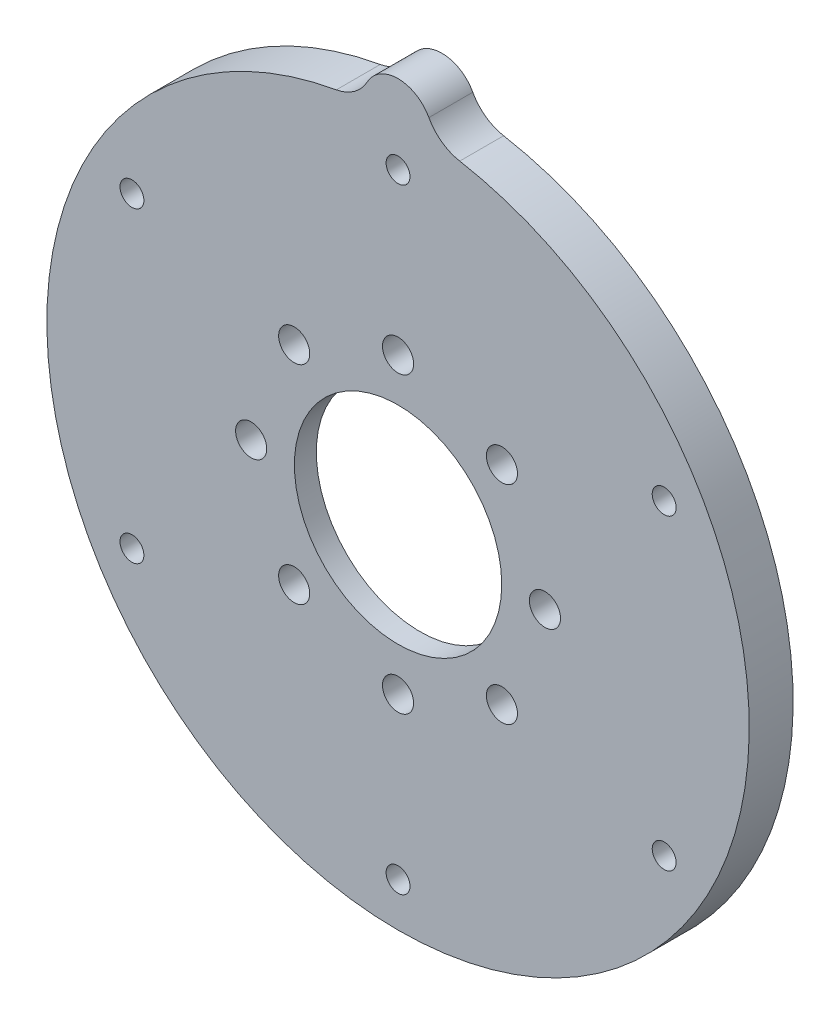
SolidWorks part; units mm, degrees
material "6061 Alloy"
ref_plane "Front Plane" through (0, 0, 0) normal (0, 0, 1) x (1, 0, 0)
ref_plane "Top Plane" through (0, 0, 0) normal (0, 1, 0) x (1, 0, 0)
ref_plane "Right Plane" through (0, 0, 0) normal (1, 0, 0) x (0, 0, -1)
sketch "Sketch1" plane through (0, 0, 0) normal (0, 0, 1) x (1, 0, 0)
  circle A0 centre (0, 0) radius 50.8
  circle A1 centre (0, 0) radius 15
  dimension "D1" = 101.6
  dimension "D2" = 30
extrude "Boss-Extrude1" add sketch "Sketch1" along normal blind 6.35
hole_wizard "M4 Clearance Hole1" positions "Sketch3" profile "Sketch4" hole size "M4" standard "Ansi Metric"
sketch "Sketch3" plane through (0, 0, 6.35) normal (0, 0, 1) x (1, 0, 0)
  point P0 (0, 21.25)
  dimension "D1" = 21.25
sketch "Sketch4" plane through (0, 21.25, 6.35) normal (1, 0, 0) x (0, -1, 0)
  line L0 (0, 0) -> (0, 26.7519)
  line L1 (0, 26.7519) -> (2.25, 25.4)
  line L2 (2.25, 25.4) -> (2.25, 0)
  line L5 (2.25, 0) -> (0, 0)
  line L10 (0, 26.7519) -> (-2.25, 25.4) construction
  line L11 (0, -6.35) -> (0, 107.95) construction
  dimension "Hole Dia." = 4.5
  dimension "Hole Depth" = 25.4
  dimension "Drill Angle" = 118
pattern_circular "CirPattern1" count 8 over 360 about axis through (0, 0, 0) along (0, 0, 1) of "M4 Clearance Hole1"
sketch "Sketch5" plane through (0, 0, 0) normal (0, 0, -1) x (-1, 0, 0)
  circle A0 centre (0, 0) radius 41.25
  dimension "D1" = 82.5
extrude "Cut-Extrude1" cut sketch "Sketch5" against normal offset from surface (3.175 mm away) 3.175 up to face at (-12.776, 15.026, 6.35)
chamfer "Chamfer1" distance 0.7874 angle 45 1 edges at (-41.25, 0, 0)
hole_wizard "#8-32 Tapped Hole1" positions "Sketch7" profile "Sketch8" tap size "#8-32" standard "Ansi Inch" end condition through all
sketch "Sketch7" plane through (0, 0, 6.35) normal (0, 0, 1) x (1, 0, 0)
  line L2 (0, 0) -> (0, 44.45) construction
  point P0 (0, 44.45)
  dimension "D1" = 44.45
sketch "Sketch8" plane through (0, 44.45, 6.35) normal (1, 0, 0) x (0, -1, 0)
  line L0 (0, 0) -> (0, 6.35)
  line L1 (0, 6.35) -> (1.7272, 6.35)
  line L2 (1.7272, 6.35) -> (1.7272, 0)
  line L5 (1.7272, 0) -> (0, 0)
  line L11 (0, -6.35) -> (0, 107.95) construction
  dimension "Thread Major Dia." = 3.4544
  dimension "Thru Tap Drill Depth" = 6.35
pattern_circular "CirPattern2" count 6 over 360 about axis through (0, 0, 0) along (0, 0, 1) of "#8-32 Tapped Hole1"
sketch "Sketch10" plane through (0, 0, 6.35) normal (0, 0, 1) x (1, 0, 0)
  line L0 (0, 50.8) -> (0, 0) construction
  arc A0 (5.0736, 50.546) -> (-5.0736, 50.546) centre (0, 50.8) ccw
  circle A1 centre (0, 0) radius 50.8 construction
  arc A2 (5.0736, 50.546) -> (-5.0736, 50.546) centre (0, 0) ccw
  dimension "D1" = 10.16
extrude "Boss-Extrude3" add sketch "Sketch10" against normal up to surface (6.35 mm away) up to face at (-36.7676, 22.225, 0)
fillet "Fillet2" radius 6.35 2 edges at (5.0736, 50.546, 3.175) (-5.0736, 50.546, 3.175)
